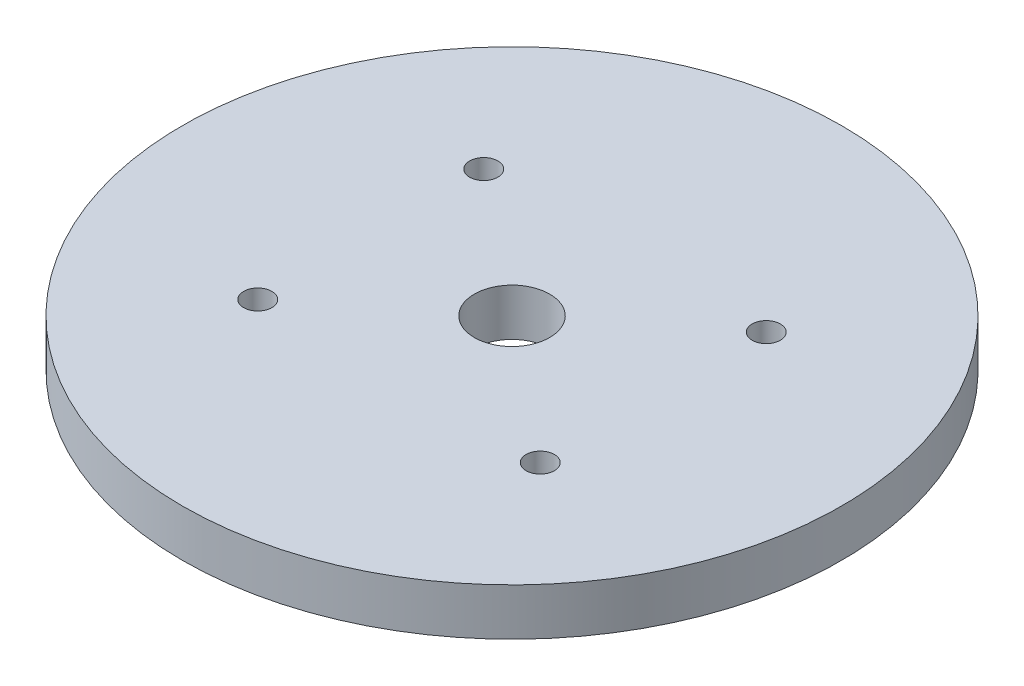
SolidWorks part; units mm, degrees
ref_plane "Front Plane" through (0, 0, 0) normal (0, 0, 1) x (1, 0, 0)
ref_plane "Top Plane" through (0, 0, 0) normal (0, 1, 0) x (1, 0, 0)
ref_plane "Right Plane" through (0, 0, 0) normal (1, 0, 0) x (0, 0, -1)
sketch "Sketch1" plane through (0, 0, 0) normal (0, 1, 0) x (1, 0, 0)
  circle A0 centre (0, 0) radius 35
  circle A1 centre (0, 0) radius 4
  dimension "D1" = 8
  dimension "D2" = 70
extrude "Boss-Extrude1" add sketch "Sketch1" along normal blind 5
sketch "Sketch2" plane through (0, 5, 0) normal (0, 1, 0) x (1, 0, 0)
  line L0 (-15, 12) -> (15, -12)
  line L1 (-15, 12) -> (15, 12)
  line L2 (-15, 12) -> (-15, -12)
  line L3 (-15, -12) -> (15, -12)
  line L4 (15, 12) -> (15, -12)
  line L5 (-15, -12) -> (15, 12)
  circle A0 centre (-15, 12) radius 1.5
  circle A1 centre (15, 12) radius 1.5
  circle A2 centre (-15, -12) radius 1.5
  circle A3 centre (15, -12) radius 1.5
  point P4 (0, 0)
  dimension "D3" = 3
  dimension "D1" = 24
  dimension "D2" = 30
extrude "Cut-Extrude1" cut sketch "Sketch2" against normal blind 167 contours L2 A2 L3 | L5 A2 L2 | L3 A2 L5 | L1 A0 L2 | L0 A0 L1 | L2 A0 L0 | L4 A1 L1 | L5 A1 L4 | L1 A1 L5 | L3 A3 L4 | L0 A3 L3 | L4 A3 L0
